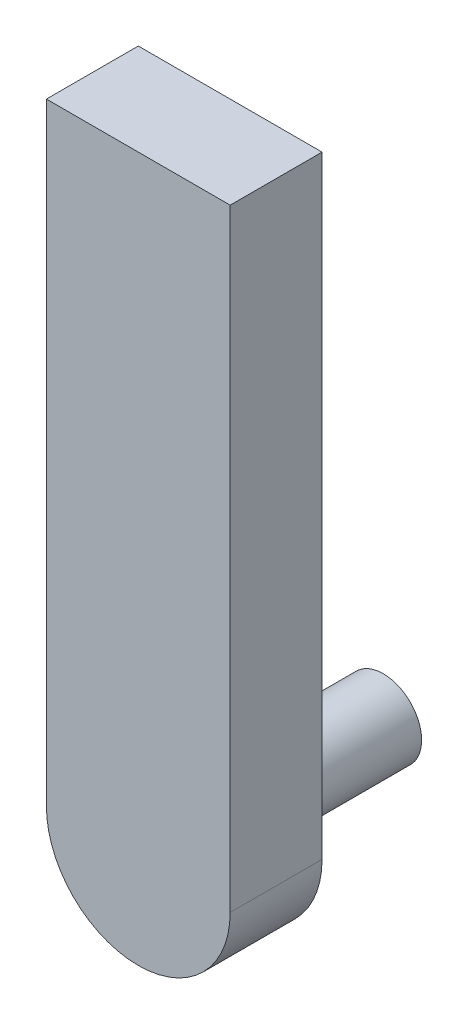
SolidWorks part; units mm, degrees
material "可鍛紅銅"
ref_plane "前基準面" through (0, 0, 0) normal (0, 0, 1) x (1, 0, 0)
ref_plane "上基準面" through (0, 0, 0) normal (0, 1, 0) x (1, 0, 0)
ref_plane "右基準面" through (0, 0, 0) normal (1, 0, 0) x (0, 0, -1)
sketch "草圖1" plane through (0, 0, 0) normal (0, 0, 1) x (1, 0, 0)
  line L0 (-6, 40) -> (-6, 0)
  line L1 (6, 0) -> (6, 40)
  line L2 (-6, 40) -> (6, 40)
  arc A0 (-6, 0) -> (6, 0) centre (0, 0) ccw
  dimension "D1" = 6
  dimension "D2" = 40
extrude "伸長1" add sketch "草圖1" along normal blind 6
sketch "草圖2" plane through (0, 0, 0) normal (0, 0, -1) x (-1, 0, 0)
  circle A0 centre (0, 0) radius 2.5
  dimension "D1" = 5
extrude "伸長2" add sketch "草圖2" along normal blind 10
